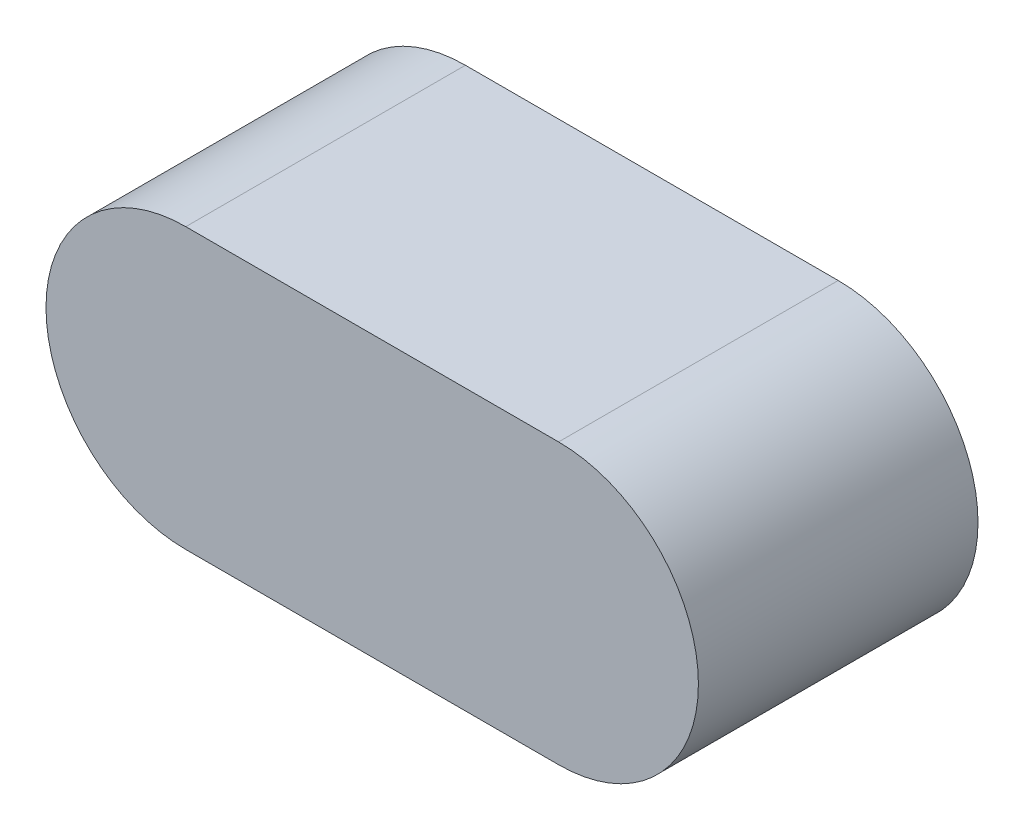
SolidWorks part; units mm, degrees
material "Plain Carbon Steel"
ref_plane "Front Plane" through (0, 0, 0) normal (0, 0, 1) x (1, 0, 0)
ref_plane "Top Plane" through (0, 0, 0) normal (0, 1, 0) x (1, 0, 0)
ref_plane "Right Plane" through (0, 0, 0) normal (1, 0, 0) x (0, 0, -1)
sketch "Sketch1" plane through (0, 0, 0) normal (0, 0, 1) x (1, 0, 0)
  line L0 (0, 0) -> (4, 0) construction
  line L1 (0, 1.5) -> (4, 1.5)
  line L2 (0, -1.5) -> (4, -1.5)
  line L3 (-1.5, 0) -> (-1.5, 2.8173) construction
  line L4 (5.5, 0) -> (5.5, 2.8173) construction
  arc A0 (0, 1.5) -> (0, -1.5) centre (0, 0) ccw
  arc A1 (4, -1.5) -> (4, 1.5) centre (4, 0) ccw
  point P3 (2, 0)
  dimension "D1" = 3
  dimension "D2" = 7
extrude "Boss-Extrude1" add sketch "Sketch1" along normal blind 3
